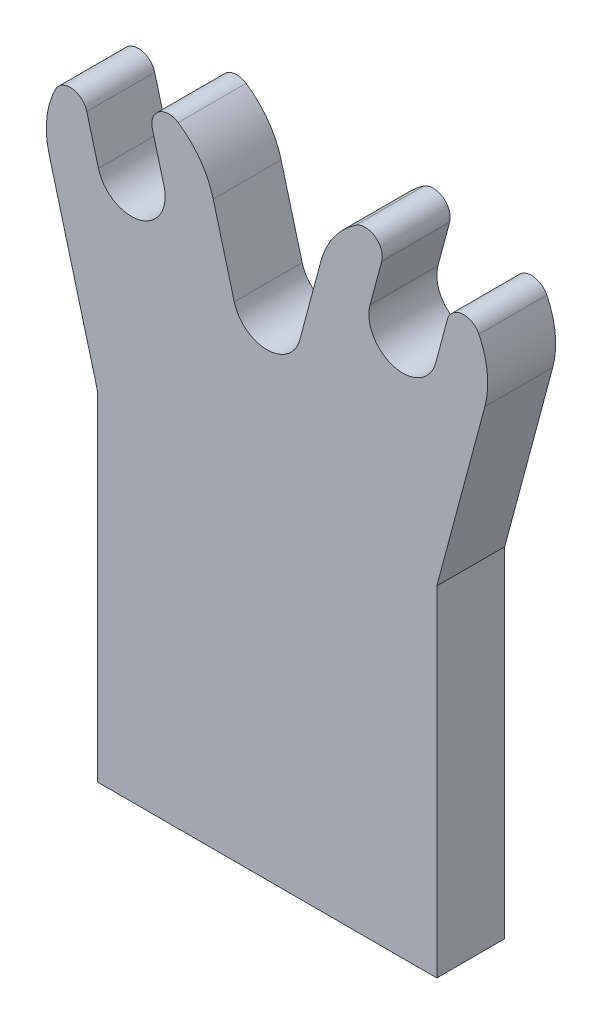
SolidWorks part; units mm, degrees
ref_plane "Front Plane" through (0, 0, 0) normal (0, 0, 1) x (1, 0, 0)
ref_plane "Top Plane" through (0, 0, 0) normal (0, 1, 0) x (1, 0, 0)
ref_plane "Right Plane" through (0, 0, 0) normal (1, 0, 0) x (0, 0, -1)
sketch "Sketch1" plane through (0, 0, 0) normal (0, 0, 1) x (1, 0, 0)
  line L0 (-5, 5) -> (-6.4148, 10.2802)
  line L1 (5, -5) -> (-5, -5)
  line L2 (5, -5) -> (5, 5)
  line L4 (-5, -5) -> (-5, 5)
  line L5 (5, -5) -> (-5, 5) construction
  line L6 (5, 5) -> (-5, -5) construction
  line L7 (0, 0) -> (0, 5.6583) construction
  line L8 (-1.5852, 11.5743) -> (0, 5.6583)
  line L9 (1.5852, 11.5743) -> (0, 5.6583)
  line L10 (5, 5) -> (6.4148, 10.2802)
  line L11 (-3.6271, 13.3992) -> (-3.0341, 11.186)
  line L12 (-4.647, 13.342) -> (-4, 10.9272) construction
  line L13 (-5.559, 12.8816) -> (-4.9659, 10.6684)
  line L14 (5.559, 12.8816) -> (4.9659, 10.6684)
  line L15 (3.6271, 13.3992) -> (3.0341, 11.186)
  arc A0 (-6.4148, 10.2802) -> (-1.5852, 11.5743) centre (-4, 10.9272) cw
  arc A1 (6.4148, 10.2802) -> (1.5852, 11.5743) centre (4, 10.9272) ccw
  arc A2 (-3.0341, 11.186) -> (-4.9659, 10.6684) centre (-4, 10.9272) cw
  arc A3 (3.0341, 11.186) -> (4.9659, 10.6684) centre (4, 10.9272) ccw
  point P0 (0, 0)
  point P16 (0, 0)
  point P20 (-4.5, 7.0834)
  point P21 (-4.1456, 6.4293)
  point P22 (-4.2564, 6.7934)
  point P23 (-4.2564, 6.718)
  dimension "D1" = 8
  dimension "D4" = 2
  dimension "D2" = 15
  dimension "D3" = 5
  dimension "D5" = 10
  dimension "D6" = 10
extrude "Boss-Extrude1" add sketch "Sketch1" along normal blind 2 contours A3 L15 A1 L9 L8 A0 L11 A2 L13 L0 L4 L1 L2 L10 L14
fillet "Fillet1" radius 0.5 4 edges at (5.559, 12.8816, 1) (3.6271, 13.3992, 1) (-3.6271, 13.3992, 1) (-5.559, 12.8816, 1)
fillet "Fillet2" radius 1 1 edges at (0, 5.6583, 1)
